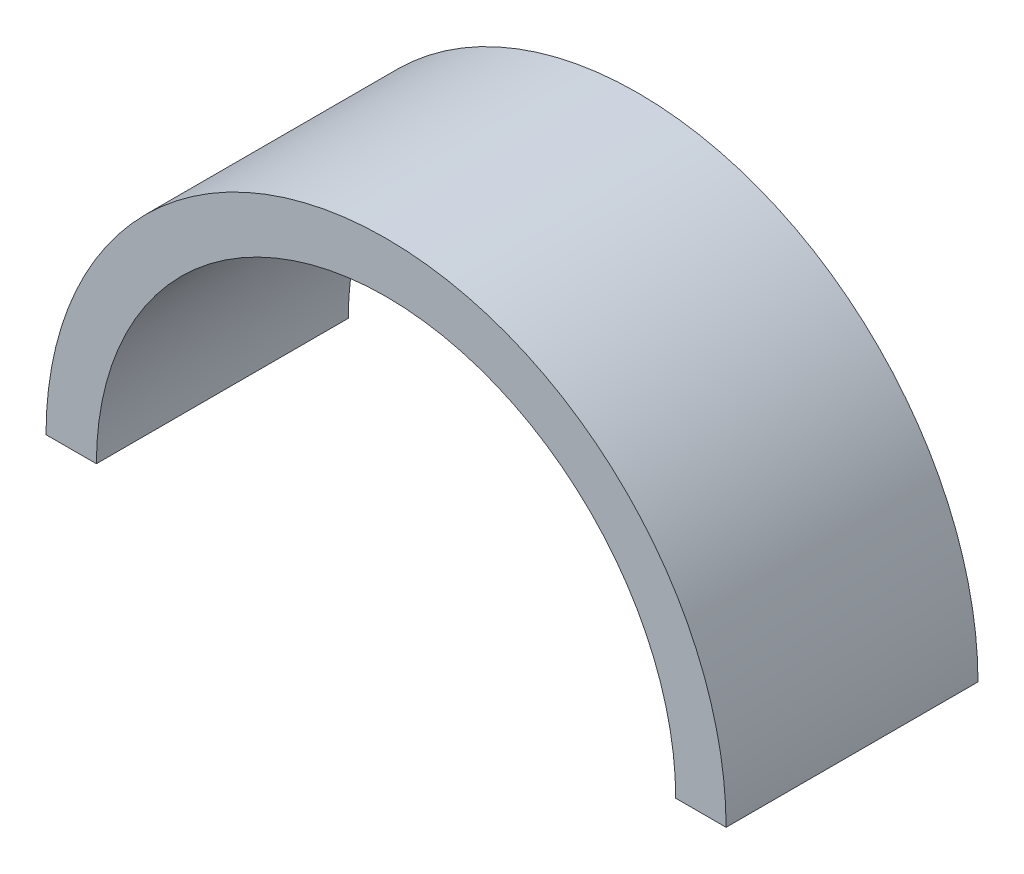
SolidWorks part; units mm, degrees
ref_plane "Front Plane" through (0, 0, 0) normal (0, 0, 1) x (1, 0, 0)
ref_plane "Top Plane" through (0, 0, 0) normal (0, 1, 0) x (1, 0, 0)
ref_plane "Right Plane" through (0, 0, 0) normal (1, 0, 0) x (0, 0, -1)
sketch "Sketch1" plane through (0, 0, 0) normal (0, 0, 1) x (1, 0, 0)
  line L0 (54, 27) -> (50, 27)
  line L1 (4, 27) -> (0, 27)
  arc A0 (0, 27) -> (54, 27) centre (27, 27) cw
  arc A1 (50, 27) -> (4, 27) centre (27, 27) ccw
  dimension "D1" = 27
  dimension "D2" = 23
extrude "Profile" add sketch "Sketch1" along normal blind 20
equation "\"Profile_Depth\"= 20mm"
equation "\"D1@Profile\" = \"Profile_Depth\""
equation "\"Profile_Sketch_1\"= 27mm"
equation "\"D1@Sketch1\" = \"Profile_Sketch_1\""
equation "\"Profile_Sketch_2\"= 23mm"
equation "\"D2@Sketch1\" = \"Profile_Sketch_2\""
equation "\"EnvelopeWidth\"= 54mm"
equation "\"EnvelopeHeight\"= 54mm"
